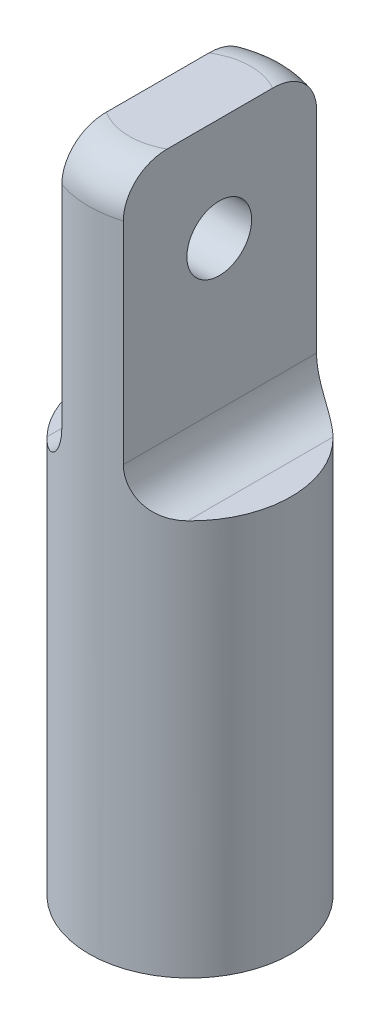
SolidWorks part; units mm, degrees
ref_plane "Спереди" through (0, 0, 0) normal (0, 0, 1) x (1, 0, 0)
ref_plane "Сверху" through (0, 0, 0) normal (0, 1, 0) x (1, 0, 0)
ref_plane "Справа" through (0, 0, 0) normal (1, 0, 0) x (0, 0, -1)
sketch "Эскиз1" plane through (0, 0, 0) normal (0, 1, 0) x (1, 0, 0)
  circle A0 centre (0, 0) radius 12.5
extrude "Вытянуть1" add sketch "Эскиз1" along normal blind 85 from offset 25
sketch "Эскиз2" plane through (0, 0, 0) normal (0, 0, 1) x (1, 0, 0)
  line L0 (0, 60) -> (0, 63.1215) construction
  line L2 (16.0544, 23.9299) -> (3.7, 23.9299)
  line L3 (-16.0544, 65.9299) -> (-4, 65.9299)
  line L4 (-16.0544, 65.9299) -> (-16.0544, 23.9299)
  line L5 (-16.0544, 23.9299) -> (-4, 23.9299)
  line L6 (-4, 65.9299) -> (-4, 23.9299)
  line L7 (3.7, 65.9299) -> (3.7, 23.9299)
  line L8 (16.0544, 65.9299) -> (3.7, 65.9299)
  line L9 (16.0544, 65.9299) -> (16.0544, 23.9299)
  dimension "D1" = 4
  dimension "D2" = 3.7
extrude "Вытянуть2" cut sketch "Эскиз2" against normal mid plane 60
fillet "Скругление2" radius 5 2 edges at (-0.1577, 60, -12.499) (-0.1577, 60, 12.499)
sketch "Эскиз3" plane through (-4, 0, 0) normal (-1, 0, 0) x (0, 0, 1)
  circle A0 centre (0.0825, 47.2276) radius 4
extrude "Вырез-Вытянуть1" cut sketch "Эскиз3" against normal through all
fillet "Скругление3" radius 5 2 edges at (3.7, 23.9299, 0) (-4, 23.9299, 0)
